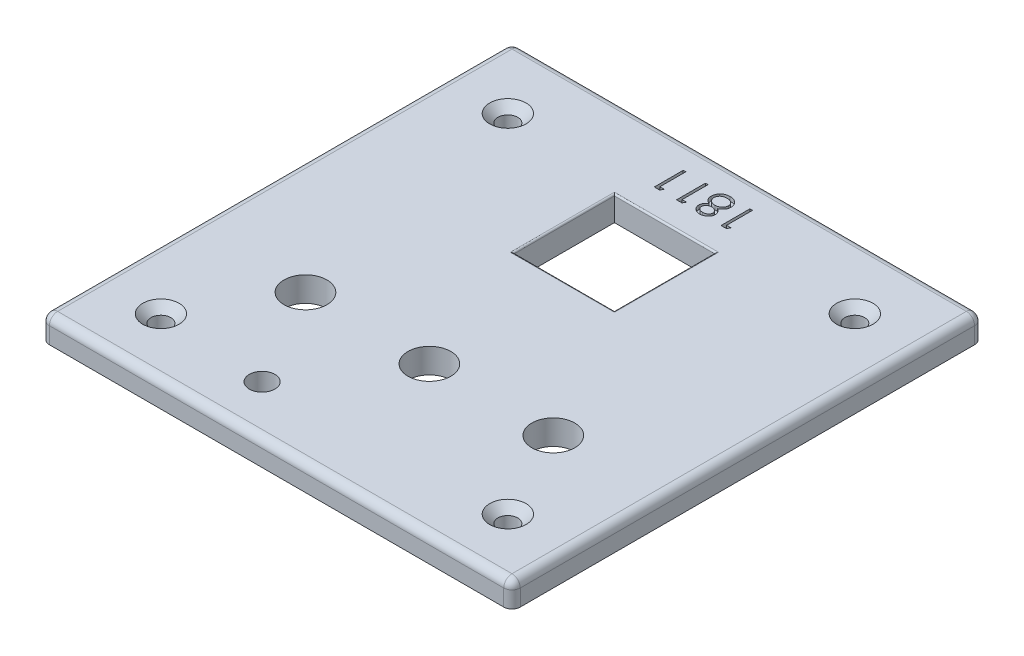
SolidWorks part; units mm, degrees
ref_plane "Plan de face" through (0, 0, 0) normal (0, 0, 1) x (1, 0, 0)
ref_plane "Plan de dessus" through (0, 0, 0) normal (0, 1, 0) x (1, 0, 0)
ref_plane "Plan de droite" through (0, 0, 0) normal (1, 0, 0) x (0, 0, -1)
sketch "Esquisse1" plane through (0, 0, 0) normal (0, 1, 0) x (1, 0, 0)
  line L1 (-29.9798, 40.399) -> (27.0202, 40.399)
  line L2 (-29.9798, 40.399) -> (-29.9798, -16.601)
  line L3 (-29.9798, -16.601) -> (27.0202, -16.601)
  line L4 (27.0202, 40.399) -> (27.0202, -16.601)
extrude "Boss.-Extru.1" add sketch "Esquisse1" along normal blind 3
sketch "Esquisse2" plane through (0, 3, 0) normal (0, 1, 0) x (1, 0, 0)
  line L0 (27.0202, -16.601) -> (27.0202, 40.399) construction
  line L1 (-29.9798, -16.601) -> (27.0202, -16.601) construction
  line L2 (-29.9798, 40.399) -> (-29.9798, -16.601) construction
  line L3 (27.0202, 40.399) -> (-29.9798, 40.399) construction
  circle A0 centre (19.5202, -9.601) radius 1.15
  circle A1 centre (-22.4798, -9.601) radius 1.15
  circle A2 centre (-22.4798, 32.399) radius 1.15
  circle A3 centre (19.5202, 32.399) radius 1.15
  dimension "D1" = 7.5
  dimension "D3" = 7.5
  dimension "D5" = 7.5
  dimension "D7" = 7.5
  dimension "D2" = 7
  dimension "D4" = 7
  dimension "D6" = 8
  dimension "D8" = 8
extrude "Enlèv. mat.-Extru.1" cut sketch "Esquisse2" against normal blind 3
sketch "Esquisse3" plane through (0, 3, 0) normal (0, 1, 0) x (1, 0, 0)
  line L0 (-29.9798, -16.601) -> (27.0202, -16.601) construction
  line L1 (-29.9798, 40.399) -> (-29.9798, -16.601) construction
  circle A0 centre (-9.2298, -10.601) radius 1.55
  dimension "D1" = 6
  dimension "D2" = 20.75
extrude "Enlèv. mat.-Extru.2" cut sketch "Esquisse3" against normal blind 3
sketch "Esquisse4" plane through (0, 3, 0) normal (0, 1, 0) x (1, 0, 0)
  line L1 (-7.5798, 30.399) -> (4.6202, 30.399)
  line L2 (-7.5798, 30.399) -> (-7.5798, 18.199)
  line L3 (-7.5798, 18.199) -> (4.6202, 18.199)
  line L4 (4.6202, 30.399) -> (4.6202, 18.199)
  line L5 (27.0202, 40.399) -> (-29.9798, 40.399) construction
  line L6 (-29.9798, 40.399) -> (-29.9798, -16.601) construction
  line L7 (-29.9798, -16.601) -> (27.0202, -16.601) construction
  line L8 (27.0202, -16.601) -> (27.0202, 40.399) construction
  circle A0 centre (-0.9798, 1.399) radius 2.6
  circle A2 centre (-15.9798, 1.399) radius 2.6
  circle A3 centre (14.0202, 1.399) radius 2.6
  dimension "D3" = 18
  dimension "D4" = 18
  dimension "D7" = 18
  dimension "D1" = 10
  dimension "D2" = 22.4
  dimension "D5" = 15
  dimension "D6" = 28
  dimension "D8" = 15
extrude "Enlèv. mat.-Extru.3" cut sketch "Esquisse4" against normal blind 3
hole_wizard "Fraisage pour vis à tête fraisée M22" positions "Esquisse7" profile "Esquisse8" countersink size "M2" standard "Ansi Metric" end condition through all
sketch "Esquisse7" plane through (0, 3, 0) normal (0, 1, 0) x (1, 0, 0)
  point P0 (19.5202, -9.601)
  point P3 (-22.4798, -9.601)
  point P6 (-22.4798, 32.399)
  point P9 (19.5202, 32.399)
sketch "Esquisse8" plane through (19.5202, 3, 9.601) normal (1, 0, 0) x (0, 0, 1)
  line L0 (0, 0) -> (0, 3)
  line L1 (0, 3) -> (1.2, 3)
  line L2 (1.2, 3) -> (1.2, 1)
  line L3 (1.2, 1) -> (2.2, 0)
  line L5 (2.2, 0) -> (0, 0)
  line L6 (-1.2, 1) -> (-2.2, 0) construction
  line L11 (0, -6.35) -> (0, 107.95) construction
  dimension "Diamètre du perçage jusqu'au prochain" = 2.4
  dimension "Profondeur du perçage jusqu'au prochain" = 3
  dimension "Diamètre du fraisage entrant" = 4.4
  dimension "Angle du fraisage entrant" = 90
fillet "Congé1" radius 1 1 edges at (-1.4798, 3, 16.601)
fillet "Congé2" radius 1 3 edges at (-29.9798, 1, 16.601) (-29.9798, 2.7071, 16.3081) (-29.9798, 3, -12.399)
fillet "Congé3" radius 1 3 edges at (27.0202, 1, 16.601) (27.0202, 2.7071, 16.3081) (27.0202, 3, -12.399)
fillet "Congé4" radius 1 5 edges at (27.0202, 1, -40.399) (26.7273, 2.7071, -40.399) (-29.9798, 1, -40.399) (-29.687, 2.7071, -40.399) (-1.4798, 3, -40.399)
fillet "Congé5" radius 0.2 1 edges at (-1.4798, 3, -30.399)
fillet "Congé6" radius 0.2 1 edges at (-7.5798, 3, -24.399)
fillet "Congé7" radius 0.2 1 edges at (4.6202, 3, -24.399)
fillet "Congé8" radius 0.2 1 edges at (-1.4798, 3, -18.199)
sketch "Esquisse10" plane through (-9.2, 3, 0) normal (0, 1, 0) x (1, 0, 0)
  text T0 "<r180>1181</r>"
extrude "Enlèv. mat.-Extru.4" cut sketch "Esquisse10" against normal blind 0.5
